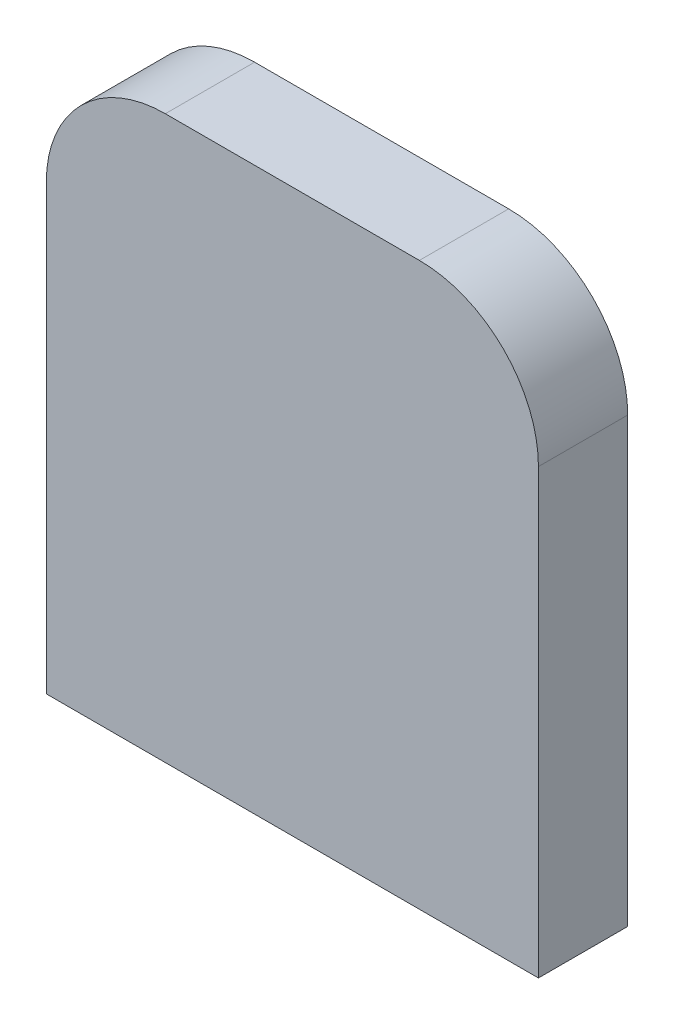
SolidWorks part; units mm, degrees
ref_plane "Front Plane" through (0, 0, 0) normal (0, 0, 1) x (1, 0, 0)
ref_plane "Top Plane" through (0, 0, 0) normal (0, 1, 0) x (1, 0, 0)
ref_plane "Right Plane" through (0, 0, 0) normal (1, 0, 0) x (0, 0, -1)
sketch "Sketch1" plane through (0, 0, 0) normal (0, 0, 1) x (1, 0, 0)
  line L2 (0, 4.9021) -> (16.5367, 4.9021)
  line L3 (0, 4.9021) -> (0, 19.7841)
  line L4 (4, 23.7841) -> (12.5367, 23.7841)
  line L5 (16.5367, 4.9021) -> (16.5367, 19.7841)
  arc A0 (12.5367, 23.7841) -> (16.5367, 19.7841) centre (12.5367, 19.7841) cw
  arc A1 (4, 23.7841) -> (0, 19.7841) centre (4, 19.7841) ccw
  dimension "D1" = 4
extrude "Boss-Extrude1" add sketch "Sketch1" along normal blind 3
